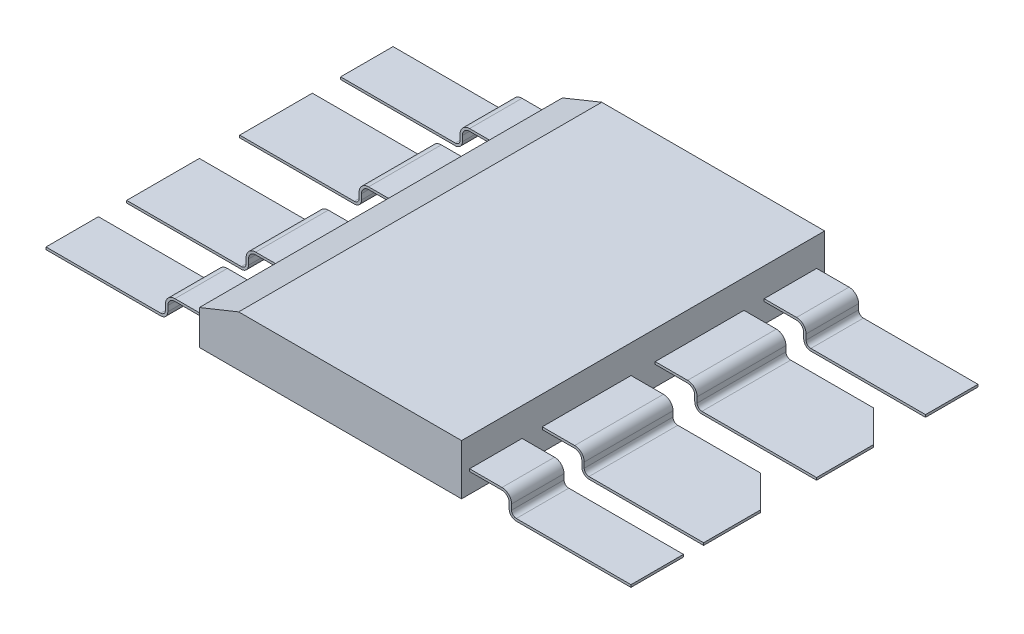
SolidWorks part; units mm, degrees
ref_plane "Спереди" through (0, 0, 0) normal (0, 0, 1) x (1, 0, 0)
ref_plane "Сверху" through (0, 0, 0) normal (0, 1, 0) x (1, 0, 0)
ref_plane "Справа" through (0, 0, 0) normal (1, 0, 0) x (0, 0, -1)
sketch "Эскиз1" plane through (0, 0, 0) normal (0, 1, 0) x (1, 0, 0)
  line L1 (-8.255, 11.43) -> (8.255, 11.43)
  line L2 (-8.255, 11.43) -> (-8.255, -11.43)
  line L3 (-8.255, -11.43) -> (8.255, -11.43)
  line L4 (8.255, 11.43) -> (8.255, -11.43)
  line L5 (-8.255, 11.43) -> (8.255, -11.43) construction
  line L6 (-8.255, -11.43) -> (8.255, 11.43) construction
  point P0 (0, 0)
extrude "Бобышка-Вытянуть1" add sketch "Эскиз1" along normal blind 3.18
chamfer "Фаска1" distance 1 angle 68 1 edges at (-8.255, 3.18, 0)
sketch "Эскиз2" plane through (8.255, 0, 0) normal (1, 0, 0) x (0, 0, -1)
  line L0 (-0.76, 1.39) -> (0.76, 1.39) construction
  line L1 (-10.925, 1.39) -> (-7.62, 1.39)
  line L2 (-10.925, 1.39) -> (-10.925, 1.24)
  line L3 (-10.925, 1.24) -> (-7.62, 1.24)
  line L4 (-7.62, 1.39) -> (-7.62, 1.24)
  line L5 (-10.925, 1.39) -> (-7.62, 1.24) construction
  line L6 (-10.925, 1.24) -> (-7.62, 1.39) construction
  line L7 (-6.35, 1.39) -> (-0.76, 1.39)
  line L8 (-6.35, 1.39) -> (-6.35, 1.24)
  line L9 (-6.35, 1.24) -> (-0.76, 1.24)
  line L10 (-0.76, 1.39) -> (-0.76, 1.24)
  line L11 (-6.35, 1.39) -> (-0.76, 1.24) construction
  line L12 (-6.35, 1.24) -> (-0.76, 1.39) construction
  line L13 (0.76, 1.39) -> (6.35, 1.39)
  line L14 (0.76, 1.39) -> (0.76, 1.24)
  line L15 (0.76, 1.24) -> (6.35, 1.24)
  line L16 (6.35, 1.39) -> (6.35, 1.24)
  line L17 (0.76, 1.39) -> (6.35, 1.24) construction
  line L18 (0.76, 1.24) -> (6.35, 1.39) construction
  line L19 (7.62, 1.39) -> (10.925, 1.39)
  line L20 (7.62, 1.39) -> (7.62, 1.24)
  line L21 (7.62, 1.24) -> (10.925, 1.24)
  line L22 (10.925, 1.39) -> (10.925, 1.24)
  line L23 (7.62, 1.39) -> (10.925, 1.24) construction
  line L24 (7.62, 1.24) -> (10.925, 1.39) construction
  line L25 (0, 0) -> (0, 3.8317) construction
  line L26 (-11.43, 0) -> (11.43, 0) construction
  point P0 (-9.2725, 1.315)
  point P5 (-3.555, 1.315)
  point P10 (3.555, 1.315)
  point P15 (9.2725, 1.315)
  point P24 (0, 1.39)
  dimension "D1" = 21.85
  dimension "D2" = 1.27
  dimension "D3" = 1.52
  dimension "D4" = 1.27
  dimension "D5" = 0
  dimension "D6" = 10.925
  dimension "D7" = 5.59
  dimension "D8" = 5.59
  dimension "D9" = 3.305
  dimension "D10" = 3.305
  dimension "D11" = 1.24
  dimension "D12" = 0
  dimension "D13" = 0
  dimension "D14" = 0
  dimension "D15" = 0.15
  dimension "D16" = 0.15
  dimension "D17" = 0.15
  dimension "D18" = 0.15
sketch "Эскиз3" plane through (0, 0, 0) normal (0, 0, 1) x (1, 0, 0)
  line L0 (10.7462, 0.79) -> (10.7462, 0.45)
  line L3 (11.1962, 0) -> (18.415, 0)
  line L4 (10.2962, 1.24) -> (8.255, 1.24)
  line L5 (8.255, 1.24) -> (8.255, 1.39) construction
  line L6 (8.255, 0) -> (8.255, 3.8317) construction
  arc A0 (10.7462, 0.45) -> (11.1962, 0) centre (11.1962, 0.45) ccw
  arc A1 (10.2962, 1.24) -> (10.7462, 0.79) centre (10.2962, 0.79) cw
  dimension "D1" = 0.45
sweep "По траектории1" add profiles "Эскиз2" path "Эскиз3"
sketch "Эскиз4" plane through (-8.255, 0, 0) normal (-1, 0, 0) x (0, 0, 1)
  line L0 (-1.27, 1.39) -> (1.27, 1.39) construction
  line L1 (-10.925, 1.39) -> (-7.625, 1.39)
  line L2 (-10.925, 1.39) -> (-10.925, 1.24)
  line L3 (-10.925, 1.24) -> (-7.625, 1.24)
  line L4 (-7.625, 1.39) -> (-7.625, 1.24)
  line L5 (-10.925, 1.39) -> (-7.625, 1.24) construction
  line L6 (-10.925, 1.24) -> (-7.625, 1.39) construction
  line L7 (-5.845, 1.39) -> (-1.27, 1.39)
  line L8 (-5.845, 1.39) -> (-5.845, 1.24)
  line L9 (-5.845, 1.24) -> (-1.27, 1.24)
  line L10 (-1.27, 1.39) -> (-1.27, 1.24)
  line L11 (-5.845, 1.39) -> (-1.27, 1.24) construction
  line L12 (-5.845, 1.24) -> (-1.27, 1.39) construction
  line L13 (1.27, 1.39) -> (5.845, 1.39)
  line L14 (1.27, 1.39) -> (1.27, 1.24)
  line L15 (1.27, 1.24) -> (5.845, 1.24)
  line L16 (5.845, 1.39) -> (5.845, 1.24)
  line L17 (1.27, 1.39) -> (5.845, 1.24) construction
  line L18 (1.27, 1.24) -> (5.845, 1.39) construction
  line L19 (7.625, 1.39) -> (10.925, 1.39)
  line L20 (7.625, 1.39) -> (7.625, 1.24)
  line L21 (7.625, 1.24) -> (10.925, 1.24)
  line L22 (10.925, 1.39) -> (10.925, 1.24)
  line L23 (7.625, 1.39) -> (10.925, 1.24) construction
  line L24 (7.625, 1.24) -> (10.925, 1.39) construction
  line L25 (0, 0) -> (0, 3.8317) construction
  line L27 (-11.43, 0) -> (11.43, 0) construction
  point P0 (-9.275, 1.315)
  point P5 (-3.5575, 1.315)
  point P10 (3.5575, 1.315)
  point P15 (9.275, 1.315)
  point P24 (0, 1.39)
  dimension "D1" = 21.85
  dimension "D2" = 1.78
  dimension "D3" = 2.54
  dimension "D4" = 1.78
  dimension "D5" = 0
  dimension "D6" = 10.925
  dimension "D7" = 3.3
  dimension "D8" = 4.575
  dimension "D9" = 3.3
  dimension "D10" = 1.24
  dimension "D11" = 0
  dimension "D12" = 0
  dimension "D13" = 0
  dimension "D14" = 0
  dimension "D15" = 0.15
  dimension "D16" = 0.15
  dimension "D17" = 0.15
  dimension "D18" = 0.15
sketch "Эскиз5" plane through (0, 0, 0) normal (0, 0, 1) x (1, 0, 0)
  line L1 (0, -1.5301) -> (0, 5.7223) construction
  line L2 (-10.2962, 1.24) -> (-8.255, 1.24)
  line L7 (-11.1962, 0) -> (-18.415, 0)
  line L8 (-10.7462, 0.79) -> (-10.7462, 0.45)
  arc A2 (-10.2962, 1.24) -> (-10.7462, 0.79) centre (-10.2962, 0.79) ccw
  arc A3 (-10.7462, 0.45) -> (-11.1962, 0) centre (-11.1962, 0.45) cw
sweep "По траектории2" add profiles "Эскиз4" path "Эскиз5"
chamfer "Фаска2" distance 2 angle 45 2 edges at (18.415, 0.075, -6.35) (18.415, 0.075, 0.76)
